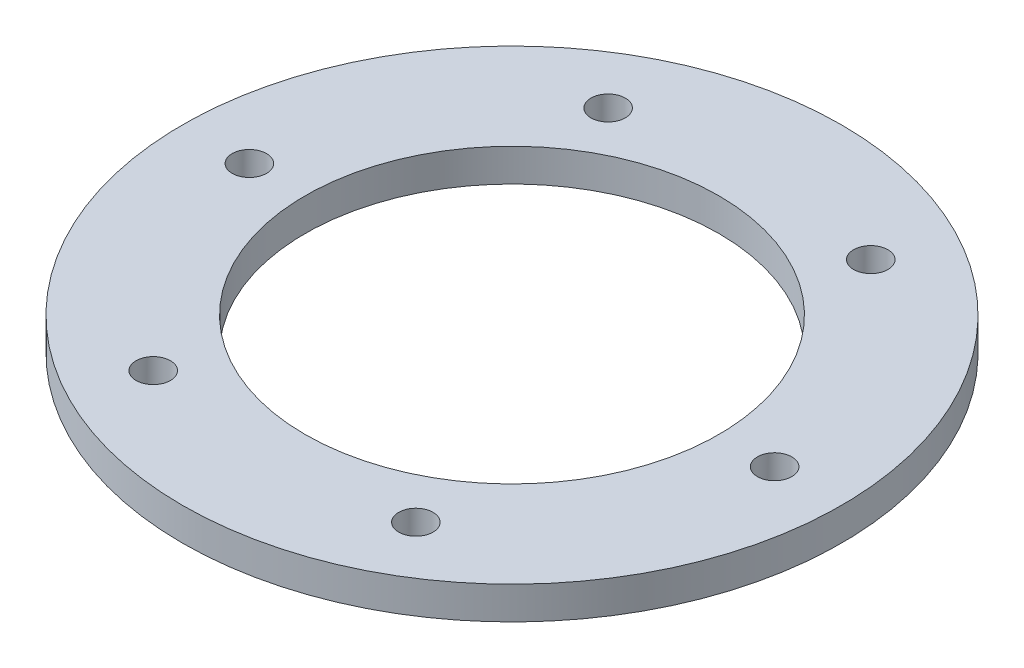
SolidWorks part; units mm, degrees
material "Thornel Mat VMA"
ref_plane "前视基准面" through (0, 0, 0) normal (0, 0, 1) x (1, 0, 0)
ref_plane "上视基准面" through (0, 0, 0) normal (0, 1, 0) x (1, 0, 0)
ref_plane "右视基准面" through (0, 0, 0) normal (1, 0, 0) x (0, 0, -1)
other "Configuration Table"
sketch "草图1" plane through (0, 0, 0) normal (0, 0, 1) x (1, 0, 0)
  line L0 (0, 0) -> (0, 12.7432) construction
  line L2 (25.28, 0) -> (40.28, 0)
  line L3 (25.28, 0) -> (25.28, 4)
  line L4 (25.28, 4) -> (40.28, 4)
  line L5 (40.28, 0) -> (40.28, 4)
  dimension "D1" = 40.28
  dimension "D2" = 15
  dimension "D3" = 4
revolve "旋转1" add sketch "草图1" angle 360 about L0
sketch "草图2" plane through (0, 4, 0) normal (0, 1, 0) x (1, 0, 0)
  line L0 (0, 0) -> (-32.1, 0) construction
  circle A0 centre (0, 0) radius 32.1 construction
  circle A1 centre (-32.1, 0) radius 2.1
  circle A3 centre (-16.05, 27.7994) radius 2.1
  circle A4 centre (16.05, 27.7994) radius 2.1
  circle A5 centre (32.1, 0) radius 2.1
  circle A6 centre (16.05, -27.7994) radius 2.1
  circle A7 centre (-16.05, -27.7994) radius 2.1
  dimension "D1" = 64.2
  dimension "D2" = 4.2
  dimension "D3" = 6
extrude "切除-拉伸1" cut sketch "草图2" against normal blind 10
